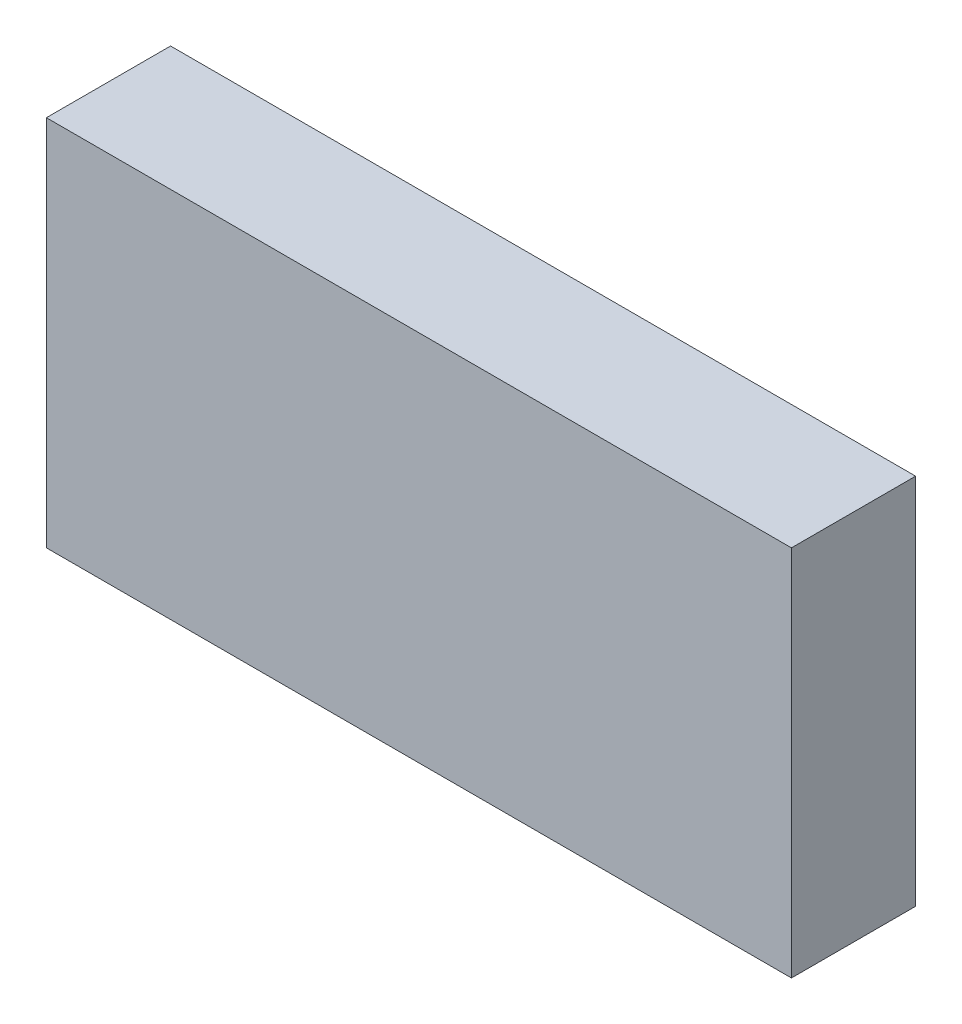
SolidWorks part; units mm, degrees
ref_plane "前视基准面" through (0, 0, 0) normal (0, 0, 1) x (1, 0, 0)
ref_plane "上视基准面" through (0, 0, 0) normal (0, 1, 0) x (1, 0, 0)
ref_plane "右视基准面" through (0, 0, 0) normal (1, 0, 0) x (0, 0, -1)
other "Configuration Table"
sketch "草图1" plane through (0, 0, 0) normal (0, 0, 1) x (1, 0, 0)
  line L1 (-60, -30) -> (60, -30)
  line L2 (-60, -30) -> (-60, 30)
  line L3 (-60, 30) -> (60, 30)
  line L4 (60, -30) -> (60, 30)
  line L5 (-60, -30) -> (60, 30) construction
  line L6 (-60, 30) -> (60, -30) construction
  point P0 (0, 0)
extrude "凸台-拉伸1" add sketch "草图1" along normal blind 20
